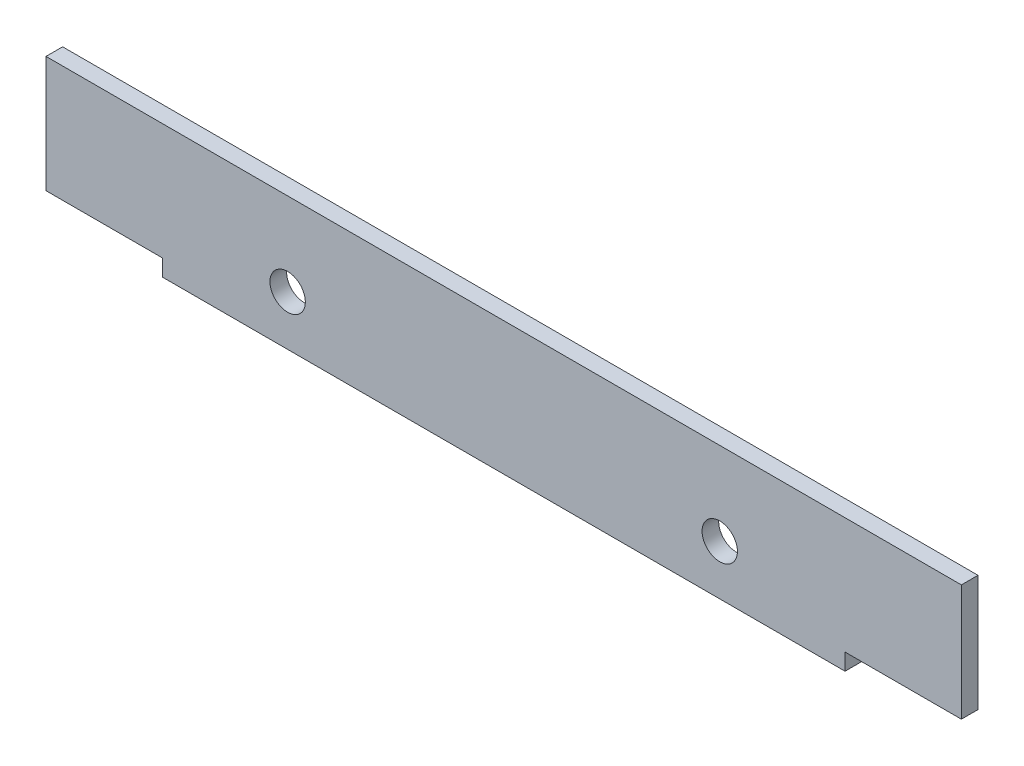
SolidWorks part; units mm, degrees
material "6061-T6 (SS)"
ref_plane "Front Plane" through (0, 0, 0) normal (0, 0, 1) x (1, 0, 0)
ref_plane "Top Plane" through (0, 0, 0) normal (0, 1, 0) x (1, 0, 0)
ref_plane "Right Plane" through (0, 0, 0) normal (1, 0, 0) x (0, 0, -1)
sketch "Sketch1" plane through (0, 0, 0) normal (0, 0, 1) x (1, 0, 0)
  line L1 (0, 0) -> (-174.879, 0)
  line L2 (0, 0) -> (0, -25.4)
  line L3 (0, -25.4) -> (-174.879, -25.4)
  line L4 (-174.879, 0) -> (-174.879, -25.4)
  dimension "D1" = 174.879
  dimension "D2" = 25.4
extrude "Boss-Extrude1" add sketch "Sketch1" along normal blind 3.175
sketch "Sketch2" plane through (0, 0, 3.175) normal (0, 0, 1) x (1, 0, 0)
  line L1 (-174.879, -25.4) -> (-152.654, -25.4)
  line L2 (-174.879, -25.4) -> (-174.879, -22.225)
  line L3 (-174.879, -22.225) -> (-152.654, -22.225)
  line L4 (-152.654, -25.4) -> (-152.654, -22.225)
  dimension "D1" = 22.225
  dimension "D2" = 3.175
extrude "Cut-Extrude1" cut sketch "Sketch2" against normal through all
ref_plane "Plane1" through (-87.4395, 0, 0) normal (-1, 0, 0) x (0, 0, 1)
mirror "Mirror1" about plane through (-87.4395, 0, 0) normal (-1, 0, 0) of "Cut-Extrude1"
sketch "Sketch3" plane through (0, 0, 3.175) normal (0, 0, 1) x (1, 0, 0)
  line L0 (-174.879, -15.875) -> (0, -15.875) construction
  line L1 (-174.879, 0) -> (-174.879, -22.225) construction
  line L2 (0, -22.225) -> (0, 0) construction
  line L3 (-152.654, -25.4) -> (-22.225, -25.4) construction
  dimension "D1" = 9.525
hole_wizard "1/4 Clearance Hole1" positions "Sketch5" profile "Sketch4" hole size "1/4" standard "Ansi Inch" end condition through all
sketch "Sketch5" plane through (0, 0, 3.175) normal (0, 0, 1) x (1, 0, 0)
  line L0 (-174.879, -15.875) -> (0, -15.875) construction
  line L1 (-87.4395, 0) -> (-87.4395, -25.4) construction
  line L2 (0, 0) -> (-174.879, 0) construction
  line L3 (-152.654, -25.4) -> (-22.225, -25.4) construction
  point P1 (-46.1645, -15.875)
  point P5 (-128.7145, -15.875)
  dimension "D1" = 82.55
  dimension "D2" = 41.275
sketch "Sketch4" plane through (-46.1645, -15.875, 3.175) normal (1, 0, 0) x (0, -1, 0)
  line L0 (0, 0) -> (0, 3.175)
  line L1 (0, 3.175) -> (3.3782, 3.175)
  line L2 (3.3782, 3.175) -> (3.3782, 0)
  line L5 (3.3782, 0) -> (0, 0)
  line L11 (0, -6.35) -> (0, 107.95) construction
  dimension "Thru Hole Dia." = 6.7564
  dimension "Thru Hole Depth" = 3.175
